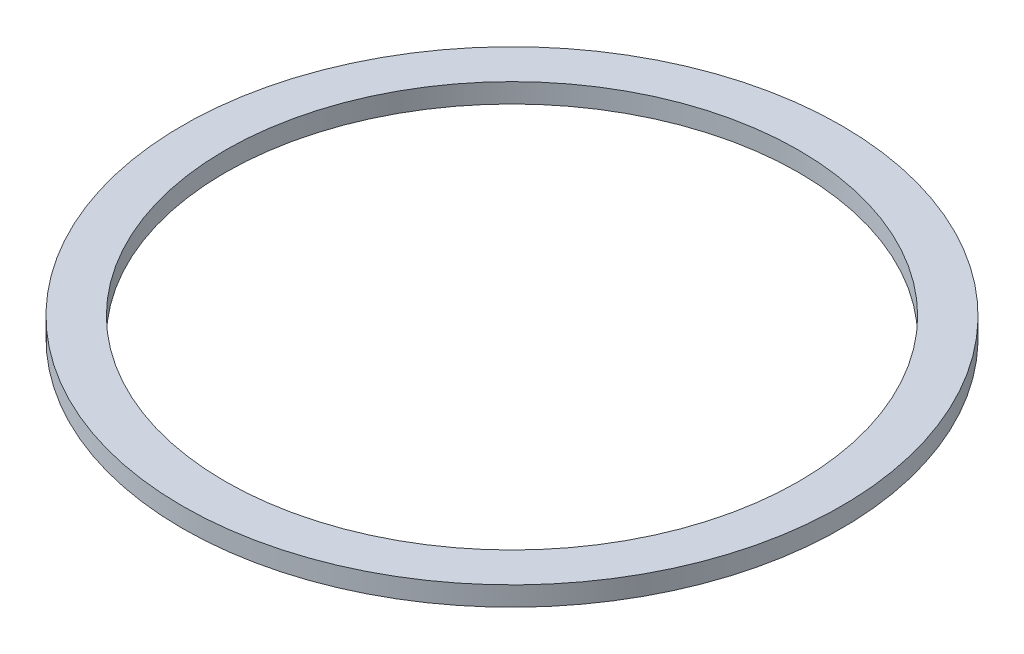
SolidWorks part; units mm, degrees
material "NEOPRENE"
ref_plane "Front Plane" through (0, 0, 0) normal (0, 0, 1) x (1, 0, 0)
ref_plane "Top Plane" through (0, 0, 0) normal (0, 1, 0) x (1, 0, 0)
ref_plane "Right Plane" through (0, 0, 0) normal (1, 0, 0) x (0, 0, -1)
sketch "Sketch1" plane through (0, 0, 0) normal (0, 1, 0) x (1, 0, 0)
  circle A0 centre (0, 0) radius 23.5
  circle A1 centre (0, 0) radius 27
  dimension "D1" = 54
  dimension "D2" = 47
extrude "Boss-Extrude1" add sketch "Sketch1" along normal blind 1.5875
